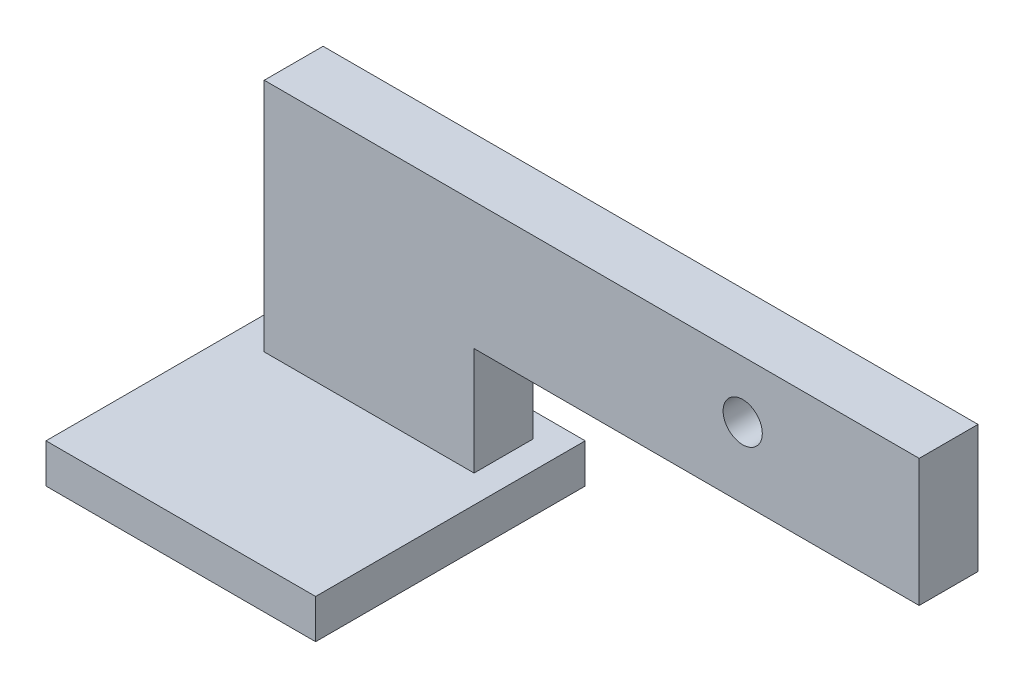
SolidWorks part; units mm, degrees
material "Aluminum Bronze"
ref_plane "Front Plane" through (0, 0, 0) normal (0, 0, 1) x (1, 0, 0)
ref_plane "Top Plane" through (0, 0, 0) normal (0, 1, 0) x (1, 0, 0)
ref_plane "Right Plane" through (0, 0, 0) normal (1, 0, 0) x (0, 0, -1)
sketch "Sketch1" plane through (0, 0, 0) normal (0, 0, 1) x (1, 0, 0)
  line L0 (0, 0) -> (0, 152.4)
  line L1 (0, 152.4) -> (424.18, 152.4)
  line L2 (424.18, 152.4) -> (424.18, 69.85)
  line L3 (424.18, 69.85) -> (135.89, 69.85)
  line L4 (135.89, 69.85) -> (135.89, 0)
  line L5 (135.89, 0) -> (0, 0)
other "Pen Sketch1" parameters "D1"=50.8085, "D2"=304.8, "D3"=110.5408, "D4"=67.4624
extrude "Boss-Extrude1" add sketch "Sketch1" along normal mid plane 38.1
sketch "Sketch2" plane through (0, 0, 19.05) normal (0, 0, 1) x (1, 0, 0)
  line L0 (424.18, 69.85) -> (424.18, 152.4) construction
  line L1 (424.18, 152.4) -> (0, 152.4) construction
  circle A0 centre (309.88, 115.57) radius 12.7
  point P2 (0, 0)
  point P3 (345.2568, 110.2925)
  dimension "D1" = 25.4
  dimension "D2" = 114.3
  dimension "D3" = 36.83
extrude "Cut-Extrude1" cut sketch "Sketch2" against normal through all
sketch "Sketch4" plane through (0, 0, 0) normal (0, -1, 0) x (1, 0, 0)
  line L0 (0, -19.05) -> (135.89, -19.05) construction
  line L1 (-20.828, 139.573) -> (153.797, 139.573)
  line L2 (-20.828, 139.573) -> (-20.828, -35.052)
  line L3 (-20.828, -35.052) -> (153.797, -35.052)
  line L4 (153.797, 139.573) -> (153.797, -35.052)
  line L5 (0, 19.05) -> (0, -19.05) construction
  dimension "D1" = 174.625
  dimension "D2" = 174.625
  dimension "D3" = 16.002
  dimension "D4" = 20.828
extrude "Boss-Extrude2" add sketch "Sketch4" along normal blind 25.4 separate body
